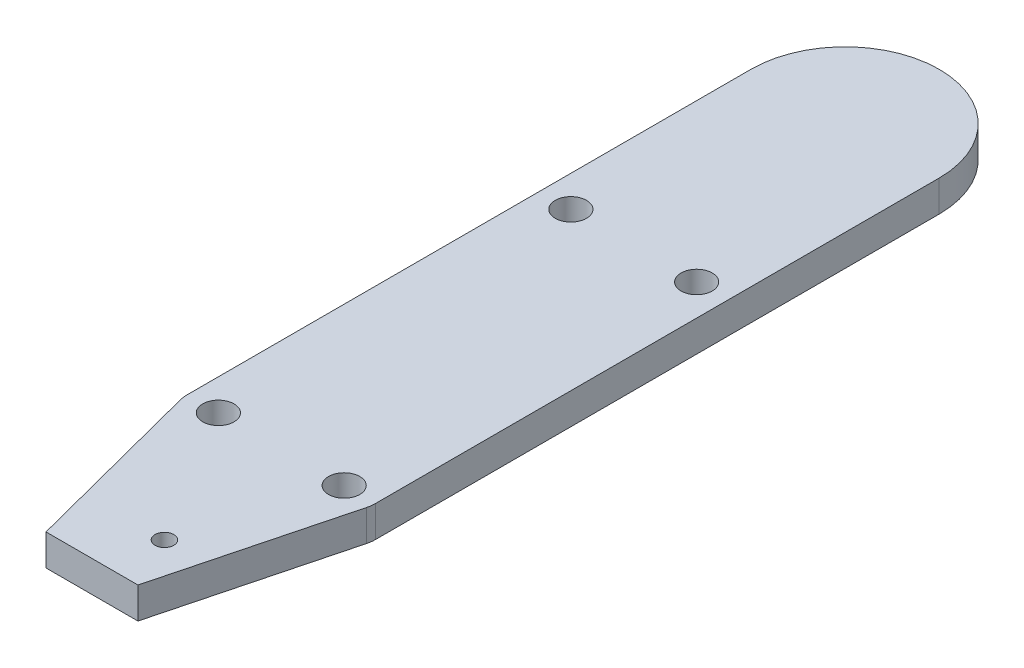
SolidWorks part; units mm, degrees
ref_plane "Front Plane" through (0, 0, 0) normal (0, 0, 1) x (1, 0, 0)
ref_plane "Top Plane" through (0, 0, 0) normal (0, 1, 0) x (1, 0, 0)
ref_plane "Right Plane" through (0, 0, 0) normal (1, 0, 0) x (0, 0, -1)
sketch "Sketch1" plane through (0, 0, 0) normal (0, 1, 0) x (1, 0, 0)
  line L0 (7.7076, -0.5032) -> (0.1608, 28.5263)
  line L1 (7.7076, -0.5032) -> (22.4211, -0.5032)
  line L2 (0, 29.7843) -> (0, 120)
  line L4 (30.1287, 29.7843) -> (30.1287, 120)
  line L6 (22.4211, -0.5032) -> (29.9678, 28.5263)
  arc A0 (30.1287, 120) -> (0, 120) centre (15.0643, 120) ccw
  arc A1 (29.9678, 28.5263) -> (30.1287, 29.7843) centre (25.1287, 29.7843) ccw
  arc A2 (0.1608, 28.5263) -> (0, 29.7843) centre (5, 29.7843) cw
  circle A4 centre (5, 29.7843) radius 2.5
  circle A5 centre (25.1287, 29.7843) radius 2.5
  circle A6 centre (25.1287, 86.1853) radius 2.5
  circle A7 centre (5, 86.1853) radius 2.5
  dimension "D1" = 5
extrude "Boss-Extrude1" add sketch "Sketch1" along normal blind 5
sketch "Sketch2" plane through (0, 5, 0) normal (0, 1, 0) x (1, 0, 0)
  circle A0 centre (18.2905, 7.8609) radius 1.5
  dimension "D1" = 3
hole_wizard "Ø3.0mm Dowel Hole3" positions "3DSketch1" profile "Sketch4" hole size "Ø3.0" standard "ANSI Metric" end condition through all
sketch3d "3DSketch1"
  point P0 (18.2905, 5, -7.8609)
sketch "Sketch4" plane through (18.2905, 5, -7.8609) normal (1, 0, 0) x (0, 0, 1)
  line L0 (0, 0) -> (0, 5)
  line L1 (0, 5) -> (1.5, 5)
  line L2 (1.5, 5) -> (1.5, 0)
  line L5 (1.5, 0) -> (0, 0)
  line L11 (0, -6.35) -> (0, 107.95) construction
  dimension "Thru Hole Dia." = 3
  dimension "Thru Hole Depth" = 5
